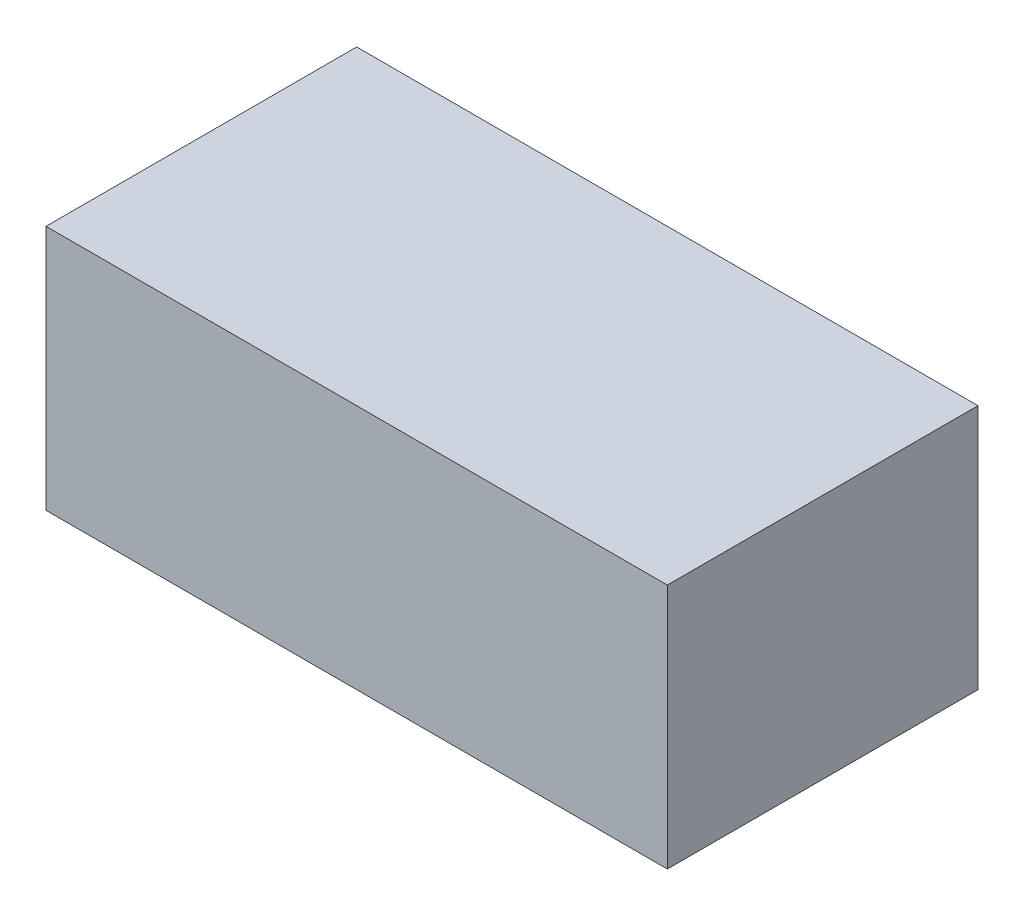
SolidWorks part; units mm, degrees
ref_plane "Front Plane" through (0, 0, 0) normal (0, 0, 1) x (1, 0, 0)
ref_plane "Top Plane" through (0, 0, 0) normal (0, 1, 0) x (1, 0, 0)
ref_plane "Right Plane" through (0, 0, 0) normal (1, 0, 0) x (0, 0, -1)
sketch "Sketch1" plane through (0, 0, 0) normal (0, 1, 0) x (1, 0, 0)
  line L1 (0, 0) -> (4.8, 0)
  line L2 (0, 0) -> (0, 2.4)
  line L3 (0, 2.4) -> (4.8, 2.4)
  line L4 (4.8, 0) -> (4.8, 2.4)
  point P5 (4.07, 2.4)
  dimension "D1" = 2.4
  dimension "D2" = 4.8
extrude "Boss-Extrude1" add sketch "Sketch1" along normal blind 1.9
